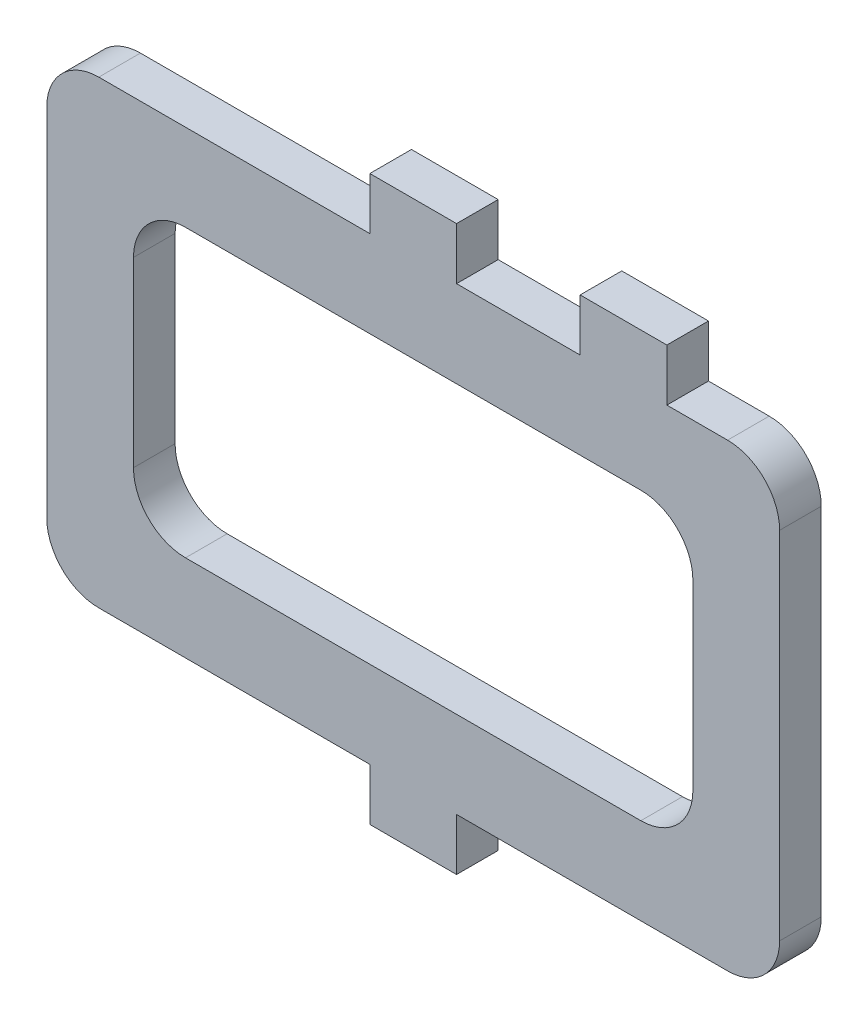
SolidWorks part; units mm, degrees
ref_plane "Alzado" through (0, 0, 0) normal (0, 0, 1) x (1, 0, 0)
ref_plane "Planta" through (0, 0, 0) normal (0, 1, 0) x (1, 0, 0)
ref_plane "Vista lateral" through (0, 0, 0) normal (1, 0, 0) x (0, 0, -1)
sketch "Croquis1" plane through (0, 0, 0) normal (0, 0, 1) x (1, 0, 0)
  line L0 (-102.6151, -90.722) -> (-86.9901, -90.722)
  line L1 (-90.4901, -61.222) -> (-90.4901, -64.222)
  line L2 (-107.6151, -61.222) -> (-105.1151, -61.222)
  line L3 (-90.4901, -64.222) -> (-86.9901, -64.222)
  line L4 (-107.6151, -90.722) -> (-123.2401, -90.722)
  line L5 (-105.1151, -61.222) -> (-102.6151, -61.222)
  line L6 (-102.6151, -61.222) -> (-102.6151, -64.222)
  line L7 (-95.4901, -61.222) -> (-95.4901, -64.222)
  line L8 (-95.4901, -64.222) -> (-102.6151, -64.222)
  line L9 (-123.2401, -64.222) -> (-107.6151, -64.222)
  line L10 (-107.6151, -90.722) -> (-107.6151, -93.722)
  line L11 (-107.6151, -93.722) -> (-102.6151, -93.722)
  line L12 (-102.6151, -93.722) -> (-102.6151, -90.722)
  line L15 (-83.9901, -87.722) -> (-83.9901, -67.222)
  line L24 (-107.6151, -61.222) -> (-107.6151, -64.222)
  line L31 (-95.4901, -61.222) -> (-90.4901, -61.222)
  line L32 (-126.2401, -87.722) -> (-126.2401, -67.222)
  arc A0 (-126.2401, -87.722) -> (-123.2401, -90.722) centre (-123.2401, -87.722) ccw
  arc A1 (-86.9901, -90.722) -> (-83.9901, -87.722) centre (-86.9901, -87.722) ccw
  arc A2 (-83.9901, -67.222) -> (-86.9901, -64.222) centre (-86.9901, -67.222) ccw
  arc A3 (-126.2401, -67.222) -> (-123.2401, -64.222) centre (-123.2401, -67.222) cw
  dimension "D1" = 3
extrude "Saliente-Extruir1" add sketch "Croquis1" along normal blind 2.4
sketch "Croquis2" plane through (0, 0, 2.4) normal (0, 0, 1) x (1, 0, 0)
  line L8 (-115.4276, -69.222) -> (-91.9901, -69.222)
  line L9 (-88.9901, -72.222) -> (-88.9901, -82.722)
  line L10 (-91.9901, -85.722) -> (-118.2401, -85.722)
  line L11 (-121.2401, -82.722) -> (-121.2401, -72.222)
  line L12 (-118.2401, -69.222) -> (-115.4276, -69.222)
  arc A0 (-118.2401, -85.722) -> (-121.2401, -82.722) centre (-118.2401, -82.722) cw
  arc A1 (-88.9901, -82.722) -> (-91.9901, -85.722) centre (-91.9901, -82.722) cw
  arc A2 (-91.9901, -69.222) -> (-88.9901, -72.222) centre (-91.9901, -72.222) cw
  arc A3 (-121.2401, -72.222) -> (-118.2401, -69.222) centre (-118.2401, -72.222) cw
  dimension "D1" = 3
extrude "Cortar-Extruir1" cut sketch "Croquis2" against normal blind 4
